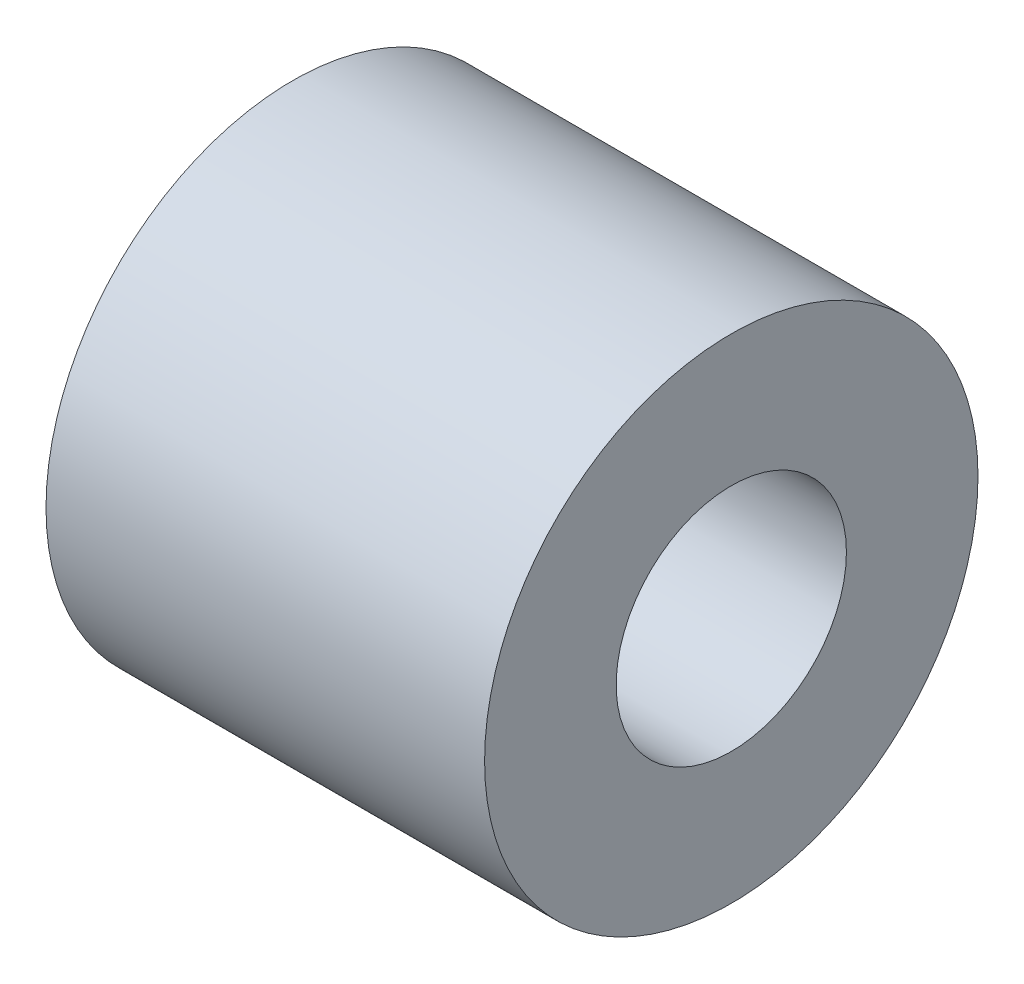
SolidWorks part; units mm, degrees
ref_plane "Front Plane" through (0, 0, 0) normal (0, 0, 1) x (1, 0, 0)
ref_plane "Top Plane" through (0, 0, 0) normal (0, 1, 0) x (1, 0, 0)
ref_plane "Right Plane" through (0, 0, 0) normal (1, 0, 0) x (0, 0, -1)
sketch "Sketch1" plane through (0, 0, 0) normal (0, 0, 1) x (1, 0, 0)
  line L0 (0, 22.5) -> (0, 10.5)
  line L1 (0, 10.5) -> (-40, 10.5)
  line L3 (-40, 10.5) -> (-40, 22.5)
  line L4 (-40, 22.5) -> (0, 22.5)
  line L5 (0, 0) -> (-40, 0) construction
  point P5 (0, 0)
  point P8 (-40, 0)
  dimension "D1" = 12
  dimension "D2" = 40
  dimension "D3" = 10.5
revolve "Revolve1" add sketch "Sketch1" angle 360 about L5
